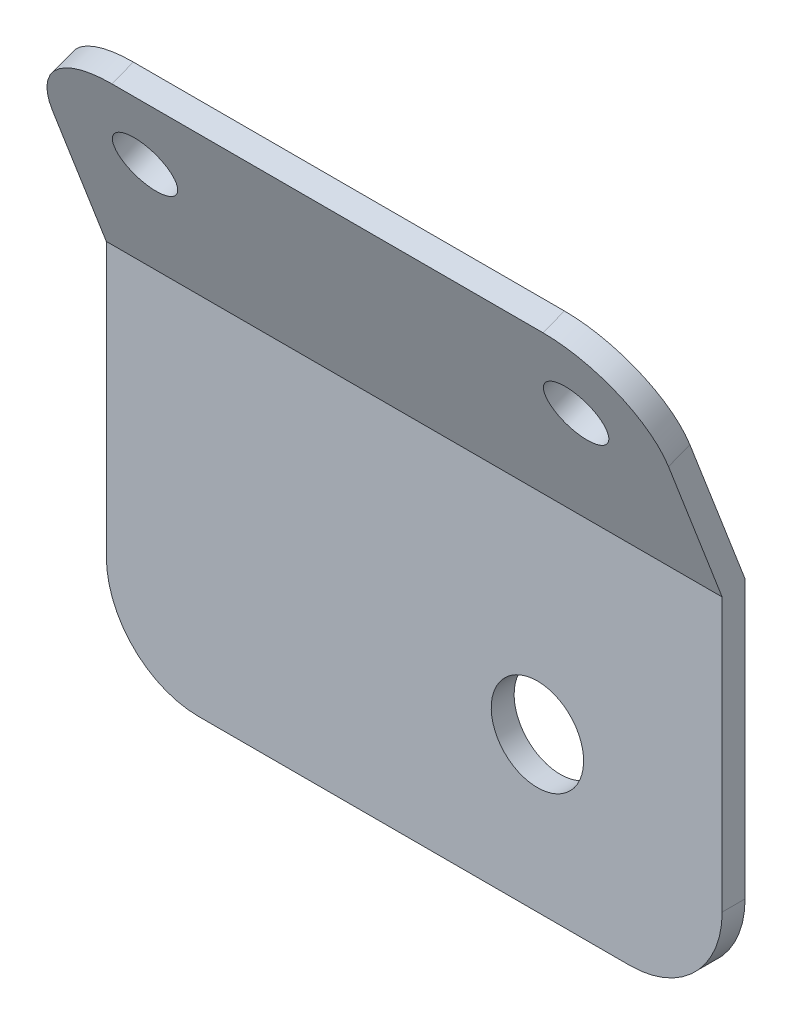
SolidWorks part; units mm, degrees
ref_plane "front" through (0, 0, 0) normal (0, 0, 1) x (1, 0, 0)
ref_plane "top" through (0, 0, 0) normal (0, 1, 0) x (1, 0, 0)
ref_plane "right" through (0, 0, 0) normal (1, 0, 0) x (0, 0, -1)
sketch "Sketch1" plane through (0, 0, 0) normal (1, 0, 0) x (0, 0, -1)
  line L0 (-9.1025, 23.7129) -> (0, 0)
  line L1 (0, 0) -> (0, -38.1)
  dimension "D1" = 25.4
  dimension "D2" = 38.1
  dimension "D3" = 21
extrude "Extrude-Thin1" add sketch "Sketch1" along normal mid plane 63.5 thin
sketch "Sketch2" plane through (0, 0, 0) normal (0, 0, -1) x (-1, 0, 0)
  line L0 (-31.75, -38.1) -> (31.75, -38.1) construction
  circle A0 centre (-12.7, -22.225) radius 4.7625
  dimension "D2" = 9.525
  dimension "D1" = 15.875
  dimension "D3" = 12.7
extrude "Cut-Extrude1" cut sketch "Sketch2" against normal through all
sketch "Sketch3" plane through (0, 0, 0) normal (0, 0.3584, -0.9336) x (-1, 0, 0)
  line L0 (0, 0) -> (0, 17.78) construction
  line L1 (-31.75, 25.4) -> (31.75, 25.4) construction
  circle A0 centre (-22.225, 15.875) radius 3.175
  circle A1 centre (22.225, 15.875) radius 3.175
  dimension "D3" = 6.35
  dimension "D1" = 44.45
  dimension "D2" = 9.525
extrude "Cut-Extrude2" cut sketch "Sketch3" against normal through all
sketch "Sketch4" plane through (0, 0, 0) normal (0, -0.3584, 0.9336) x (1, 0, 0)
  line L0 (-76.2, 15.875) -> (115.57, 15.875) construction
  circle A0 centre (-22.225, 15.875) radius 3.175 construction
  circle A1 centre (22.225, 15.875) radius 3.175 construction
  point P0 (22.225, 15.875)
  point P1 (-22.225, 15.875)
fillet "Fillet1" radius 9.525 4 edges at (-31.75, -38.1, 1.1811) (31.75, -38.1, 1.1811) (31.75, 23.2897, 10.2052) (-31.75, 23.2897, 10.2052)
